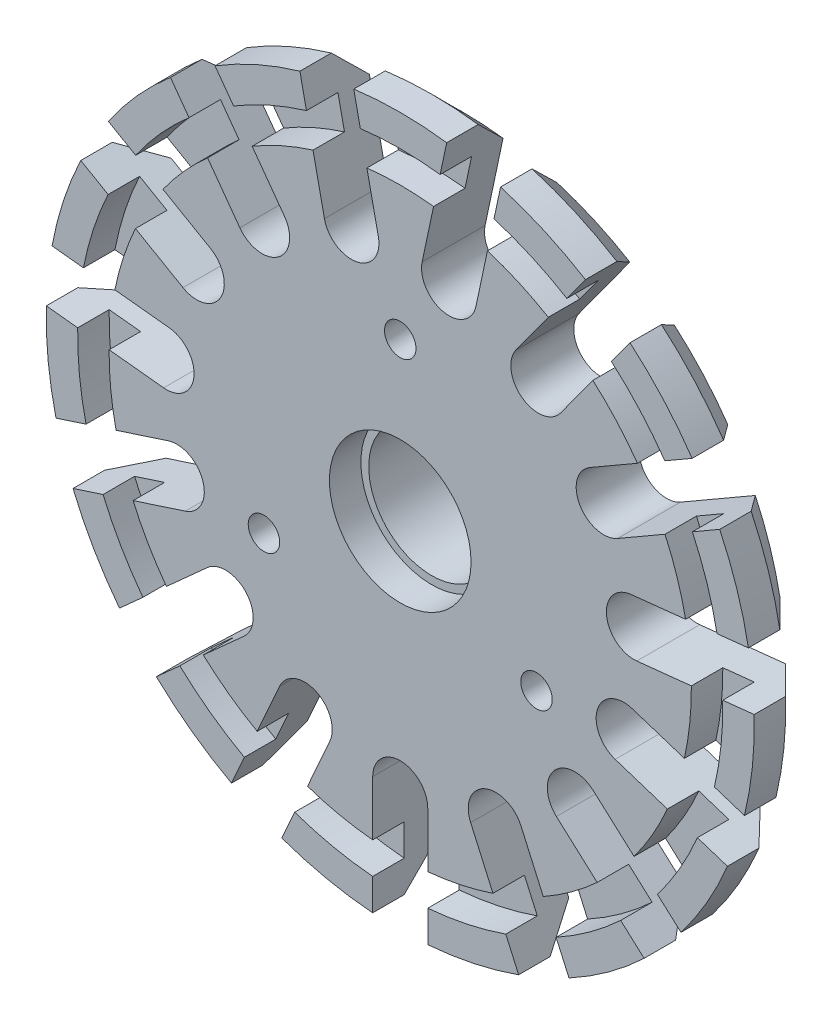
SolidWorks part; units mm, degrees
material "Liga 1060"
ref_plane "Plano frontal" through (0, 0, 0) normal (0, 0, 1) x (1, 0, 0)
ref_plane "Plano superior" through (0, 0, 0) normal (0, 1, 0) x (1, 0, 0)
ref_plane "Plano direito" through (0, 0, 0) normal (1, 0, 0) x (0, 0, -1)
sketch "Esboço1" plane through (0, 0, 0) normal (0, 0, 1) x (1, 0, 0)
  line L0 (0, 0) -> (0, -6) construction
  line L1 (-0.45, -5.9831) -> (0.45, -5.9831) construction
  line L2 (-0.45, -5.9831) -> (-0.45, -6.2831)
  line L3 (0.45, -5.9831) -> (0.45, -6.2831)
  line L4 (-1.6841, -5.7588) -> (-1.7465, -6.0522)
  line L5 (-0.8038, -5.9459) -> (-0.8662, -6.2394)
  line L7 (-2.8446, -5.2828) -> (-2.9667, -5.5569)
  line L8 (-2.0225, -5.6489) -> (-2.1445, -5.9229)
  line L10 (-3.8808, -4.5759) -> (-4.0572, -4.8186)
  line L11 (-3.1527, -5.1049) -> (-3.3291, -5.3476)
  line L13 (-4.7474, -3.6691) -> (-4.9704, -3.8698)
  line L14 (-4.1452, -4.3379) -> (-4.3681, -4.5386)
  line L16 (-5.4065, -2.6018) -> (-5.6663, -2.7518)
  line L17 (-4.9565, -3.3813) -> (-5.2163, -3.5313)
  line L19 (-5.8293, -1.4209) -> (-6.1146, -1.5136)
  line L20 (-5.5512, -2.2769) -> (-5.8365, -2.3696)
  line L22 (-5.9974, -0.1779) -> (-6.2957, -0.2092)
  line L23 (-5.9033, -1.0729) -> (-6.2016, -1.1043)
  line L25 (-5.9033, 1.0729) -> (-6.2016, 1.1043)
  line L26 (-5.9974, 0.1779) -> (-6.2957, 0.2092)
  line L28 (-5.5512, 2.2769) -> (-5.8365, 2.3696)
  line L29 (-5.8293, 1.4209) -> (-6.1146, 1.5136)
  line L31 (-4.9565, 3.3813) -> (-5.2163, 3.5313)
  line L32 (-5.4065, 2.6018) -> (-5.6663, 2.7518)
  line L34 (-4.1452, 4.3379) -> (-4.3681, 4.5386)
  line L35 (-4.7474, 3.6691) -> (-4.9704, 3.8698)
  line L37 (-3.1527, 5.1049) -> (-3.3291, 5.3476)
  line L38 (-3.8808, 4.5759) -> (-4.0572, 4.8186)
  line L40 (-2.0225, 5.6489) -> (-2.1445, 5.9229)
  line L41 (-2.8446, 5.2828) -> (-2.9667, 5.5569)
  line L43 (-0.8038, 5.9459) -> (-0.8662, 6.2394)
  line L44 (-1.6841, 5.7588) -> (-1.7465, 6.0522)
  line L46 (0.45, 5.9831) -> (0.45, 6.2831)
  line L47 (-0.45, 5.9831) -> (-0.45, 6.2831)
  line L49 (1.6841, 5.7588) -> (1.7465, 6.0522)
  line L50 (0.8038, 5.9459) -> (0.8662, 6.2394)
  line L52 (2.8446, 5.2828) -> (2.9667, 5.5569)
  line L53 (2.0225, 5.6489) -> (2.1445, 5.9229)
  line L55 (3.8808, 4.5759) -> (4.0572, 4.8186)
  line L56 (3.1527, 5.1049) -> (3.3291, 5.3476)
  line L58 (4.7474, 3.6691) -> (4.9704, 3.8698)
  line L59 (4.1452, 4.3379) -> (4.3681, 4.5386)
  line L61 (5.4065, 2.6018) -> (5.6663, 2.7518)
  line L62 (4.9565, 3.3813) -> (5.2163, 3.5313)
  line L64 (5.8293, 1.4209) -> (6.1146, 1.5136)
  line L65 (5.5512, 2.2769) -> (5.8365, 2.3696)
  line L67 (5.9974, 0.1779) -> (6.2957, 0.2092)
  line L68 (5.9033, 1.0729) -> (6.2016, 1.1043)
  line L70 (5.9033, -1.0729) -> (6.2016, -1.1043)
  line L71 (5.9974, -0.1779) -> (6.2957, -0.2092)
  line L73 (5.5512, -2.2769) -> (5.8365, -2.3696)
  line L74 (5.8293, -1.4209) -> (6.1146, -1.5136)
  line L76 (4.9565, -3.3813) -> (5.2163, -3.5313)
  line L77 (5.4065, -2.6018) -> (5.6663, -2.7518)
  line L79 (4.1452, -4.3379) -> (4.3681, -4.5386)
  line L80 (4.7474, -3.6691) -> (4.9704, -3.8698)
  line L82 (3.1527, -5.1049) -> (3.3291, -5.3476)
  line L83 (3.8808, -4.5759) -> (4.0572, -4.8186)
  line L85 (2.0225, -5.6489) -> (2.1445, -5.9229)
  line L86 (2.8446, -5.2828) -> (2.9667, -5.5569)
  line L88 (0.8038, -5.9459) -> (0.8662, -6.2394)
  line L89 (1.6841, -5.7588) -> (1.7465, -6.0522)
  line L91 (0, 0) -> (-0.45, -5.9831) construction
  line L92 (0, 0) -> (-1.6841, -5.7588) construction
  line L93 (-0.8038, 5.9459) -> (-1.6841, 5.7588) construction
  line L94 (0.45, 5.9831) -> (0, 5.9831) construction
  line L95 (1.6841, 5.7588) -> (0.8038, 5.9459) construction
  line L96 (2.8446, 5.2828) -> (2.0225, 5.6489) construction
  line L97 (3.8808, 4.5759) -> (3.1527, 5.1049) construction
  line L98 (4.7474, 3.6691) -> (4.1452, 4.3379) construction
  line L99 (5.4065, 2.6018) -> (4.9565, 3.3813) construction
  line L100 (5.8293, 1.4209) -> (5.5512, 2.2769) construction
  line L101 (5.9974, 0.1779) -> (5.9033, 1.0729) construction
  line L102 (5.9033, -1.0729) -> (5.9974, -0.1779) construction
  line L103 (5.5512, -2.2769) -> (5.8293, -1.4209) construction
  line L104 (4.9565, -3.3813) -> (5.4065, -2.6018) construction
  line L105 (4.1452, -4.3379) -> (4.7474, -3.6691) construction
  line L106 (3.1527, -5.1049) -> (3.8808, -4.5759) construction
  line L107 (2.0225, -5.6489) -> (2.8446, -5.2828) construction
  line L108 (0.8038, -5.9459) -> (1.6841, -5.7588) construction
  line L109 (-1.6841, -5.7588) -> (-0.8038, -5.9459) construction
  line L110 (-2.8446, -5.2828) -> (-2.0225, -5.6489) construction
  line L111 (-3.8808, -4.5759) -> (-3.1527, -5.1049) construction
  line L112 (-4.7474, -3.6691) -> (-4.1452, -4.3379) construction
  line L113 (-5.4065, -2.6018) -> (-4.9565, -3.3813) construction
  line L114 (-5.8293, -1.4209) -> (-5.5512, -2.2769) construction
  line L115 (-5.9696, -0.4422) -> (-5.9033, -1.0729) construction
  line L116 (-2.0225, 5.6489) -> (-2.8446, 5.2828) construction
  line L117 (-3.1527, 5.1049) -> (-3.8808, 4.5759) construction
  line L118 (-4.1452, 4.3379) -> (-4.7474, 3.6691) construction
  line L119 (-4.9565, 3.3813) -> (-5.4065, 2.6018) construction
  line L120 (-5.5512, 2.2769) -> (-5.8293, 1.4209) construction
  line L121 (-5.9033, 1.0729) -> (-5.9974, 0.1779) construction
  arc A0 (-1.6841, 5.7588) -> (-2.0225, 5.6489) centre (0, 0) ccw
  circle A1 centre (0, 0) radius 7.125 construction
  arc A2 (-0.125, -7.1239) -> (0.125, -7.1239) centre (0, 0) ccw
  arc A3 (-1.7465, 6.0522) -> (-0.8662, 6.2394) centre (0, 0) ccw construction
  arc A4 (-0.45, -6.2831) -> (-0.125, -7.1239) centre (0.8001, -6.2831) ccw
  arc A5 (0.45, -6.2831) -> (0.125, -7.1239) centre (-0.8001, -6.2831) cw
  arc A6 (-1.6034, -6.9422) -> (-1.3589, -6.9942) centre (0, 0) ccw
  arc A7 (-1.7465, -6.0522) -> (-1.6034, -6.9422) centre (-0.5237, -6.3122) ccw
  arc A8 (-0.8662, -6.2394) -> (-1.3589, -6.9942) centre (-2.089, -5.9794) cw
  arc A9 (-3.0117, -6.4572) -> (-2.7834, -6.5589) centre (0, 0) ccw
  arc A10 (-2.9667, -5.5569) -> (-3.0117, -6.4572) centre (-1.8246, -6.0653) ccw
  arc A11 (-2.1445, -5.9229) -> (-2.7834, -6.5589) centre (-3.2865, -5.4145) cw
  arc A12 (-4.2885, -5.6899) -> (-4.0862, -5.8368) centre (0, 0) ccw
  arc A13 (-4.0572, -4.8186) -> (-4.2885, -5.6899) centre (-3.0458, -5.5534) ccw
  arc A14 (-3.3291, -5.3476) -> (-4.0862, -5.8368) centre (-4.3404, -4.6128) cw
  arc A15 (-5.3777, -4.6739) -> (-5.2105, -4.8597) centre (0, 0) ccw
  arc A16 (-4.9704, -3.8698) -> (-5.3777, -4.6739) centre (-4.1339, -4.7988) ccw
  arc A17 (-4.3681, -4.5386) -> (-5.2105, -4.8597) centre (-5.2046, -3.6096) cw
  arc A18 (-6.232, -3.4537) -> (-6.107, -3.6702) centre (0, 0) ccw
  arc A19 (-5.6663, -2.7518) -> (-6.232, -3.4537) centre (-5.0413, -3.8345) ccw
  arc A20 (-5.2163, -3.5313) -> (-6.107, -3.6702) centre (-5.8414, -2.4486) cw
  arc A21 (-6.8139, -2.0825) -> (-6.7366, -2.3203) centre (0, 0) ccw
  arc A22 (-6.1146, -1.5136) -> (-6.8139, -2.0825) centre (-5.7283, -2.7025) ccw
  arc A23 (-5.8365, -2.3696) -> (-6.7366, -2.3203) centre (-6.2228, -1.1806) cw
  arc A24 (-7.0979, -0.6203) -> (-7.0718, -0.869) centre (0, 0) ccw
  arc A25 (-6.2957, -0.2092) -> (-7.0979, -0.6203) centre (-6.165, -1.4525) ccw
  arc A26 (-6.2016, -1.1043) -> (-7.0718, -0.869) centre (-6.3323, 0.139) cw
  arc A27 (-7.0718, 0.869) -> (-7.0979, 0.6203) centre (0, 0) ccw
  arc A28 (-6.2016, 1.1043) -> (-7.0718, 0.869) centre (-6.3323, -0.139) ccw
  arc A29 (-6.2957, 0.2092) -> (-7.0979, 0.6203) centre (-6.165, 1.4525) cw
  arc A30 (-6.7366, 2.3203) -> (-6.8139, 2.0825) centre (0, 0) ccw
  arc A31 (-5.8365, 2.3696) -> (-6.7366, 2.3203) centre (-6.2228, 1.1806) ccw
  arc A32 (-6.1146, 1.5136) -> (-6.8139, 2.0825) centre (-5.7283, 2.7025) cw
  arc A33 (-6.107, 3.6702) -> (-6.232, 3.4537) centre (0, 0) ccw
  arc A34 (-5.2163, 3.5313) -> (-6.107, 3.6702) centre (-5.8414, 2.4486) ccw
  arc A35 (-5.6663, 2.7518) -> (-6.232, 3.4537) centre (-5.0413, 3.8345) cw
  arc A36 (-5.2105, 4.8597) -> (-5.3777, 4.6739) centre (0, 0) ccw
  arc A37 (-4.3681, 4.5386) -> (-5.2105, 4.8597) centre (-5.2046, 3.6096) ccw
  arc A38 (-4.9704, 3.8698) -> (-5.3777, 4.6739) centre (-4.1339, 4.7988) cw
  arc A39 (-4.0862, 5.8368) -> (-4.2885, 5.6899) centre (0, 0) ccw
  arc A40 (-3.3291, 5.3476) -> (-4.0862, 5.8368) centre (-4.3404, 4.6128) ccw
  arc A41 (-4.0572, 4.8186) -> (-4.2885, 5.6899) centre (-3.0458, 5.5534) cw
  arc A42 (-2.7834, 6.5589) -> (-3.0117, 6.4572) centre (0, 0) ccw
  arc A43 (-2.1445, 5.9229) -> (-2.7834, 6.5589) centre (-3.2865, 5.4145) ccw
  arc A44 (-2.9667, 5.5569) -> (-3.0117, 6.4572) centre (-1.8246, 6.0653) cw
  arc A45 (-1.3589, 6.9942) -> (-1.6034, 6.9422) centre (0, 0) ccw
  arc A46 (-0.8662, 6.2394) -> (-1.3589, 6.9942) centre (-2.089, 5.9794) ccw
  arc A47 (-1.7465, 6.0522) -> (-1.6034, 6.9422) centre (-0.5237, 6.3122) cw
  arc A48 (0.125, 7.1239) -> (-0.125, 7.1239) centre (0, 0) ccw
  arc A49 (0.45, 6.2831) -> (0.125, 7.1239) centre (-0.8001, 6.2831) ccw
  arc A50 (-0.45, 6.2831) -> (-0.125, 7.1239) centre (0.8001, 6.2831) cw
  arc A51 (1.6034, 6.9422) -> (1.3589, 6.9942) centre (0, 0) ccw
  arc A52 (1.7465, 6.0522) -> (1.6034, 6.9422) centre (0.5237, 6.3122) ccw
  arc A53 (0.8662, 6.2394) -> (1.3589, 6.9942) centre (2.089, 5.9794) cw
  arc A54 (3.0117, 6.4572) -> (2.7834, 6.5589) centre (0, 0) ccw
  arc A55 (2.9667, 5.5569) -> (3.0117, 6.4572) centre (1.8246, 6.0653) ccw
  arc A56 (2.1445, 5.9229) -> (2.7834, 6.5589) centre (3.2865, 5.4145) cw
  arc A57 (4.2885, 5.6899) -> (4.0862, 5.8368) centre (0, 0) ccw
  arc A58 (4.0572, 4.8186) -> (4.2885, 5.6899) centre (3.0458, 5.5534) ccw
  arc A59 (3.3291, 5.3476) -> (4.0862, 5.8368) centre (4.3404, 4.6128) cw
  arc A60 (5.3777, 4.6739) -> (5.2105, 4.8597) centre (0, 0) ccw
  arc A61 (4.9704, 3.8698) -> (5.3777, 4.6739) centre (4.1339, 4.7988) ccw
  arc A62 (4.3681, 4.5386) -> (5.2105, 4.8597) centre (5.2046, 3.6096) cw
  arc A63 (6.232, 3.4537) -> (6.107, 3.6702) centre (0, 0) ccw
  arc A64 (5.6663, 2.7518) -> (6.232, 3.4537) centre (5.0413, 3.8345) ccw
  arc A65 (5.2163, 3.5313) -> (6.107, 3.6702) centre (5.8414, 2.4486) cw
  arc A66 (6.8139, 2.0825) -> (6.7366, 2.3203) centre (0, 0) ccw
  arc A67 (6.1146, 1.5136) -> (6.8139, 2.0825) centre (5.7283, 2.7025) ccw
  arc A68 (5.8365, 2.3696) -> (6.7366, 2.3203) centre (6.2228, 1.1806) cw
  arc A69 (7.0979, 0.6203) -> (7.0718, 0.869) centre (0, 0) ccw
  arc A70 (6.2957, 0.2092) -> (7.0979, 0.6203) centre (6.165, 1.4525) ccw
  arc A71 (6.2016, 1.1043) -> (7.0718, 0.869) centre (6.3323, -0.139) cw
  arc A72 (7.0718, -0.869) -> (7.0979, -0.6203) centre (0, 0) ccw
  arc A73 (6.2016, -1.1043) -> (7.0718, -0.869) centre (6.3323, 0.139) ccw
  arc A74 (6.2957, -0.2092) -> (7.0979, -0.6203) centre (6.165, -1.4525) cw
  arc A75 (6.7366, -2.3203) -> (6.8139, -2.0825) centre (0, 0) ccw
  arc A76 (5.8365, -2.3696) -> (6.7366, -2.3203) centre (6.2228, -1.1806) ccw
  arc A77 (6.1146, -1.5136) -> (6.8139, -2.0825) centre (5.7283, -2.7025) cw
  arc A78 (6.107, -3.6702) -> (6.232, -3.4537) centre (0, 0) ccw
  arc A79 (5.2163, -3.5313) -> (6.107, -3.6702) centre (5.8414, -2.4486) ccw
  arc A80 (5.6663, -2.7518) -> (6.232, -3.4537) centre (5.0413, -3.8345) cw
  arc A81 (5.2105, -4.8597) -> (5.3777, -4.6739) centre (0, 0) ccw
  arc A82 (4.3681, -4.5386) -> (5.2105, -4.8597) centre (5.2046, -3.6096) ccw
  arc A83 (4.9704, -3.8698) -> (5.3777, -4.6739) centre (4.1339, -4.7988) cw
  arc A84 (4.0862, -5.8368) -> (4.2885, -5.6899) centre (0, 0) ccw
  arc A85 (3.3291, -5.3476) -> (4.0862, -5.8368) centre (4.3404, -4.6128) ccw
  arc A86 (4.0572, -4.8186) -> (4.2885, -5.6899) centre (3.0458, -5.5534) cw
  arc A87 (2.7834, -6.5589) -> (3.0117, -6.4572) centre (0, 0) ccw
  arc A88 (2.1445, -5.9229) -> (2.7834, -6.5589) centre (3.2865, -5.4145) ccw
  arc A89 (2.9667, -5.5569) -> (3.0117, -6.4572) centre (1.8246, -6.0653) cw
  arc A90 (1.3589, -6.9942) -> (1.6034, -6.9422) centre (0, 0) ccw
  arc A91 (0.8662, -6.2394) -> (1.3589, -6.9942) centre (2.089, -5.9794) ccw
  arc A92 (1.7465, -6.0522) -> (1.6034, -6.9422) centre (0.5237, -6.3122) cw
  arc A93 (-0.45, 5.9831) -> (-0.8038, 5.9459) centre (0, 0) ccw
  arc A94 (0.8038, 5.9459) -> (0.45, 5.9831) centre (0, 0) ccw
  arc A95 (2.0225, 5.6489) -> (1.6841, 5.7588) centre (0, 0) ccw
  arc A96 (3.1527, 5.1049) -> (2.8446, 5.2828) centre (0, 0) ccw
  arc A97 (4.1452, 4.3379) -> (3.8808, 4.5759) centre (0, 0) ccw
  arc A98 (4.9565, 3.3813) -> (4.7474, 3.6691) centre (0, 0) ccw
  arc A99 (5.5512, 2.2769) -> (5.4065, 2.6018) centre (0, 0) ccw
  arc A100 (5.9033, 1.0729) -> (5.8293, 1.4209) centre (0, 0) ccw
  arc A101 (5.9974, -0.1779) -> (5.9974, 0.1779) centre (0, 0) ccw
  arc A102 (5.8293, -1.4209) -> (5.9033, -1.0729) centre (0, 0) ccw
  arc A103 (5.4065, -2.6018) -> (5.5512, -2.2769) centre (0, 0) ccw
  arc A104 (4.7474, -3.6691) -> (4.9565, -3.3813) centre (0, 0) ccw
  arc A105 (3.8808, -4.5759) -> (4.1452, -4.3379) centre (0, 0) ccw
  arc A106 (2.8446, -5.2828) -> (3.1527, -5.1049) centre (0, 0) ccw
  arc A107 (1.6841, -5.7588) -> (2.0225, -5.6489) centre (0, 0) ccw
  arc A108 (0.45, -5.9831) -> (0.8038, -5.9459) centre (0, 0) ccw
  arc A109 (-0.8038, -5.9459) -> (-0.45, -5.9831) centre (0, 0) ccw
  arc A110 (-2.0225, -5.6489) -> (-1.6841, -5.7588) centre (0, 0) ccw
  arc A111 (-3.1527, -5.1049) -> (-2.8446, -5.2828) centre (0, 0) ccw
  arc A112 (-4.1452, -4.3379) -> (-3.8808, -4.5759) centre (0, 0) ccw
  arc A113 (-4.9565, -3.3813) -> (-4.7474, -3.6691) centre (0, 0) ccw
  arc A114 (-5.5512, -2.2769) -> (-5.4065, -2.6018) centre (0, 0) ccw
  arc A115 (-5.9033, -1.0729) -> (-5.8293, -1.4209) centre (0, 0) ccw
  arc A116 (-2.8446, 5.2828) -> (-3.1527, 5.1049) centre (0, 0) ccw
  arc A117 (-3.8808, 4.5759) -> (-4.1452, 4.3379) centre (0, 0) ccw
  arc A118 (-4.7474, 3.6691) -> (-4.9565, 3.3813) centre (0, 0) ccw
  arc A119 (-5.4065, 2.6018) -> (-5.5512, 2.2769) centre (0, 0) ccw
  arc A120 (-5.8293, 1.4209) -> (-5.9033, 1.0729) centre (0, 0) ccw
  arc A121 (-5.9974, 0.1779) -> (-5.9974, -0.1779) centre (0, 0) ccw
  point P11 (0, -7.125)
  dimension "D1" = 12
  dimension "D2" = 14.25
  dimension "D3" = 0.9
  dimension "D4" = 0.25
  dimension "D5" = 0.3
  dimension "D6" = 30
  dimension "D7" = 12
extrude "Ressalto-extrusão1" add sketch "Esboço1" along normal blind 4
sketch "Esboço2" plane through (0, 0, 4) normal (0, 0, 1) x (1, 0, 0)
  circle A0 centre (0, 0) radius 4
  dimension "D1" = 8
extrude "Corte-extrusão1" cut sketch "Esboço2" against normal through all
sketch "Esboço3" plane through (0, 0, 4) normal (0, 0, 1) x (1, 0, 0)
  line L0 (0, 0) -> (0, 3.4045) construction
  point P9 (0, 4.25)
  dimension "D1" = 4.25
sketch "Esboço4" plane through (0, 0, 4) normal (0, 0, 1) x (1, 0, 0)
  circle A0 centre (0, 0) radius 22.5
  dimension "D1" = 45
extrude "Ressalto-extrusão2" add sketch "Esboço4" along normal blind 4
chamfer "Chanfro1" distance 2 angle 45 1 edges at (22.5, 0, 4)
sketch "Esboço5" plane through (0, 0, 8) normal (0, 0, 1) x (1, 0, 0)
  line L0 (0, 0) -> (0, -22.5) construction
  line L1 (0, -200000) -> (0, 200003.4045) construction
  line L2 (-1.75, -22.4318) -> (-1.75, -14.9318)
  line L3 (1.75, -14.9318) -> (1.75, -22.4318)
  line L4 (-1.75, -22.4318) -> (-1.75, -22.8318)
  line L5 (-1.75, -22.8318) -> (1.75, -22.8318)
  line L6 (1.75, -22.8318) -> (1.75, -22.4318)
  circle A0 centre (0, 0) radius 22.5 construction
  arc A2 (-1.75, -14.9318) -> (1.75, -14.9318) centre (0, -14.9318) cw
  dimension "D3" = 0.4
  dimension "D1" = 3.5
  dimension "D2" = 1.75
  dimension "D4" = 7.5
extrude "Corte-extrusão2" cut sketch "Esboço5" against normal blind 4 contours L2 A2 L3 L6 L5 L4
pattern_circular "PadrãoCircular1" count 15 over 360 about axis through (0, 0, 0) along (0, 0, 1) of "Corte-extrusão2"
sketch "Esboço7" plane through (0, 0, 8) normal (0, 0, 1) x (1, 0, 0)
  circle A0 centre (0, 0) radius 4.5
  dimension "D1" = 9
extrude "Corte-extrusão3" cut sketch "Esboço7" against normal blind 2
sketch "Esboço8" plane through (0, 0, 6) normal (0, 0, 1) x (1, 0, 0)
  circle A0 centre (0, 0) radius 4
  dimension "D1" = 8
extrude "Corte-extrusão4" cut sketch "Esboço8" against normal blind 2
sketch "Esboço9" plane through (0, 0, 8) normal (0, 0, 1) x (1, 0, 0)
  circle A0 centre (0, 0) radius 20.5
  circle A1 centre (0, 0) radius 18.5
  dimension "D1" = 41
  dimension "D2" = 37
extrude "Corte-extrusão5" cut sketch "Esboço9" against normal blind 2
sketch "Esboço10" plane through (0, 0, 4) normal (0, 0, -1) x (-1, 0, 0)
  line L0 (0, 0) -> (0, 10) construction
  line L1 (0, -200000) -> (0, 200003.4045) construction
  dimension "D1" = 10
hole_wizard "Escareado para parafuso com cabeça escareada chata de M1.61" positions "3DSketch3" profile "Esboço11" countersink size "M1.6" standard "ISO" end condition through all
sketch3d "3DSketch3"
  point P0 (0, 10, 4)
sketch "Esboço11" plane through (0, 10, 4) normal (1, 0, 0) x (0, 1, 0)
  line L0 (0, 0) -> (0, 4)
  line L1 (0, 4) -> (1, 4)
  line L2 (1, 4) -> (1, 0.8)
  line L3 (1, 0.8) -> (1.8, 0)
  line L5 (1.8, 0) -> (0, 0)
  line L6 (-1, 0.8) -> (-1.8, 0) construction
  line L11 (0, -6.35) -> (0, 107.95) construction
  dimension "Thru Hole Dia." = 2
  dimension "Thru Hole Depth" = 4
  dimension "Near C'Sink Dia." = 3.6
  dimension "Near C'Sink Angle" = 90
pattern_circular "PadrãoCircular2" count 3 over 360 about axis through (0, 0, 0) along (0, 0, 1) of "Escareado para parafuso com cabeça escareada chata de M1.61"
